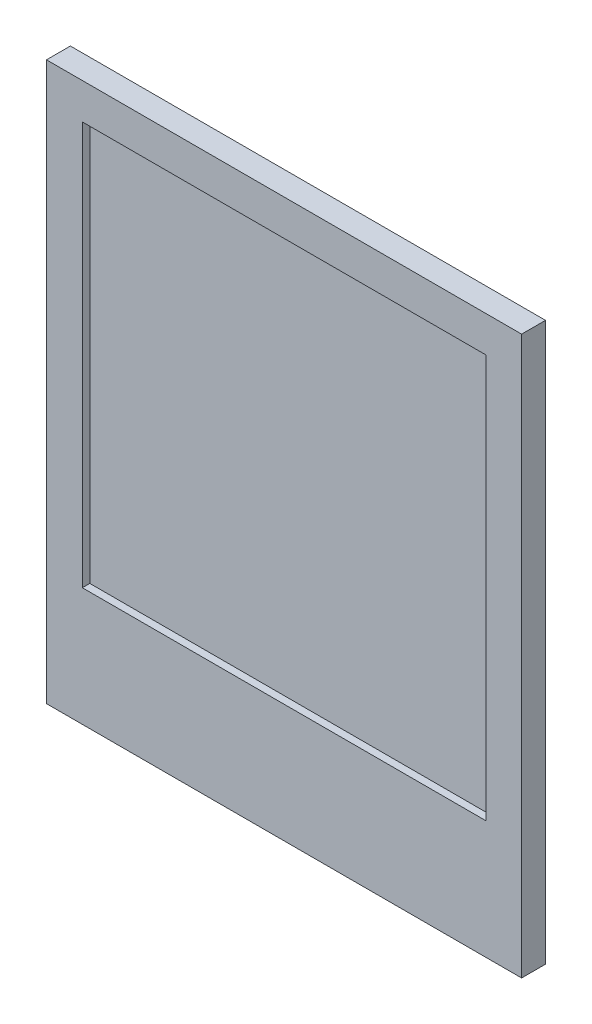
SolidWorks part; units mm, degrees
ref_plane "前视基准面" through (0, 0, 0) normal (0, 0, 1) x (1, 0, 0)
ref_plane "上视基准面" through (0, 0, 0) normal (0, 1, 0) x (1, 0, 0)
ref_plane "右视基准面" through (0, 0, 0) normal (1, 0, 0) x (0, 0, -1)
sketch "草图1" plane through (0, 0, 0) normal (0, 0, 1) x (1, 0, 0)
  line L1 (-15.9, 18.66) -> (15.9, 18.66)
  line L2 (-15.9, 18.66) -> (-15.9, -18.66)
  line L3 (-15.9, -18.66) -> (15.9, -18.66)
  line L4 (15.9, 18.66) -> (15.9, -18.66)
  line L5 (-15.9, 18.66) -> (15.9, -18.66) construction
  line L6 (-15.9, -18.66) -> (15.9, 18.66) construction
  point P0 (0, 0)
  dimension "D1" = 31.8
  dimension "D2" = 37.32
extrude "凸台-拉伸1" add sketch "草图1" along normal blind 1.6
sketch "草图2" plane through (0, 0, 1.6) normal (0, 0, 1) x (1, 0, 0)
  line L0 (15.9, -18.66) -> (15.9, 18.66) construction
  line L1 (-13.5, 16.26) -> (13.5, 16.26)
  line L2 (-13.5, 16.26) -> (-13.5, -10.74)
  line L3 (-13.5, -10.74) -> (13.5, -10.74)
  line L4 (13.5, 16.26) -> (13.5, -10.74)
  line L5 (-13.5, 16.26) -> (13.5, -10.74) construction
  line L6 (-13.5, -10.74) -> (13.5, 16.26) construction
  line L7 (15.9, 18.66) -> (-15.9, 18.66) construction
  point P0 (0.1281, 2.8881)
  dimension "D1" = 27
  dimension "D2" = 27
  dimension "D3" = 2.4
  dimension "D4" = 2.4
extrude "切除-拉伸1" cut sketch "草图2" against normal blind 0.5
